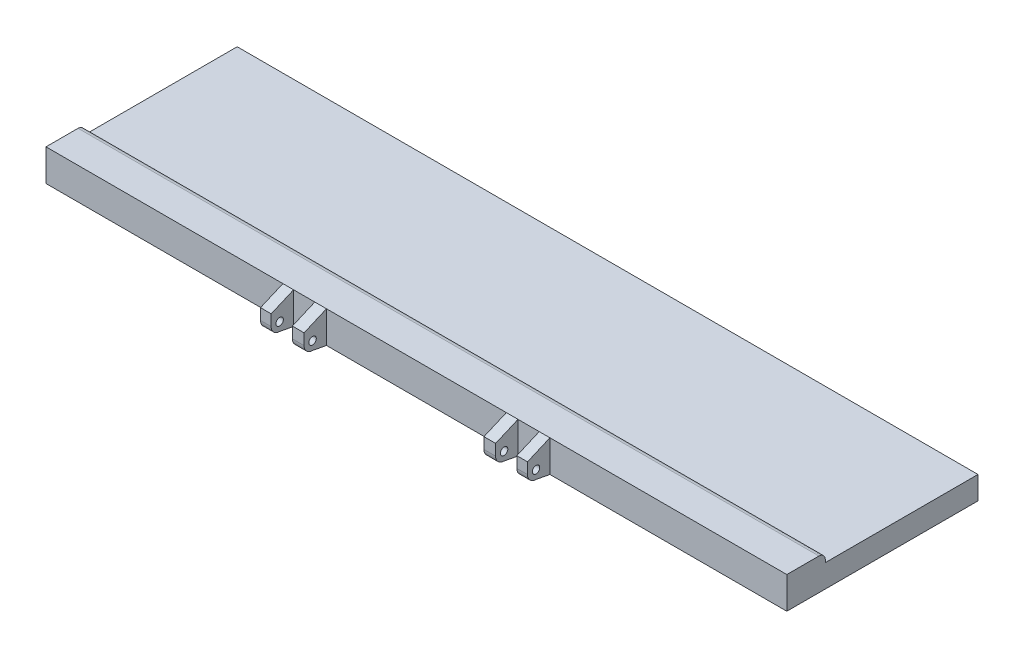
SolidWorks part; units mm, degrees
ref_plane "Front Plane" through (0, 0, 0) normal (0, 0, 1) x (1, 0, 0)
ref_plane "Top Plane" through (0, 0, 0) normal (0, 1, 0) x (1, 0, 0)
ref_plane "Right Plane" through (0, 0, 0) normal (1, 0, 0) x (0, 0, -1)
sketch "Sketch1" plane through (0, 0, 0) normal (0, 1, 0) x (1, 0, 0)
  line L0 (0, -76.945) -> (-70.693, -76.945) construction
  line L1 (-291.17, 76.945) -> (291.17, 76.945)
  line L2 (-291.17, 76.945) -> (-291.17, -76.945)
  line L3 (-291.17, -76.945) -> (291.17, -76.945)
  line L4 (291.17, 76.945) -> (291.17, -76.945)
  line L5 (-291.17, 76.945) -> (291.17, -76.945) construction
  line L6 (-291.17, -76.945) -> (291.17, 76.945) construction
  line L7 (0, 0) -> (0, -76.945) construction
  line L8 (-104.9432, -85.7514) -> (-96.5524, -85.7514) construction
  line L9 (-70.693, -76.945) -> (-104.9432, -76.945)
  line L10 (-70.693, -76.945) -> (-70.693, -94.5577)
  line L11 (-70.693, -94.5577) -> (-104.9432, -94.5577)
  line L12 (-104.9432, -76.945) -> (-104.9432, -94.5577)
  line L13 (-96.5524, -85.7514) -> (-79.8666, -85.7514) construction
  line L14 (96.5524, -94.5577) -> (79.8666, -94.5577)
  line L15 (-96.5524, -76.945) -> (-79.8666, -76.945)
  line L16 (-96.5524, -76.945) -> (-96.5524, -94.5577)
  line L17 (-96.5524, -94.5577) -> (-79.8666, -94.5577)
  line L18 (-79.8666, -76.945) -> (-79.8666, -94.5577)
  line L19 (-96.5524, -76.945) -> (-79.8666, -94.5577) construction
  line L20 (-96.5524, -94.5577) -> (-79.8666, -76.945) construction
  line L21 (79.8666, -76.945) -> (79.8666, -94.5577)
  line L22 (96.5524, -76.945) -> (79.8666, -76.945)
  line L23 (96.5524, -76.945) -> (96.5524, -94.5577)
  line L24 (70.693, -94.5577) -> (104.9432, -94.5577)
  line L25 (104.9432, -76.945) -> (104.9432, -94.5577)
  line L26 (70.693, -76.945) -> (104.9432, -76.945)
  line L27 (70.693, -76.945) -> (70.693, -94.5577)
  point P0 (0, 0)
  point P14 (-88.2095, -85.7514)
  dimension "D1" = 153.89
  dimension "D2" = 582.34
  dimension "D3" = 34.2502
extrude "Boss-Extrude1" add sketch "Sketch1" along normal blind 25 contours L4 L1 L2 L3 L9 | L25 L3 L23 L24 | L3 L27 L24 L21 | L3 L18 L11 L10 | L16 L3 L12 L11
sketch "Sketch2" plane through (104.9432, 0, 0) normal (1, 0, 0) x (0, 0, -1)
  circle A0 centre (-87.8824, 8.7487) radius 2.911
  dimension "D1" = 5.8221
extrude "Cut-Extrude1" cut sketch "Sketch2" against normal through all
sketch "Sketch3" plane through (104.9432, 0, 0) normal (1, 0, 0) x (0, 0, -1)
  line L0 (-87.8824, 2.0735) -> (-76.945, 0)
  line L1 (-76.945, 0) -> (-94.5577, 0) construction
  line L2 (-87.8824, 0) -> (-94.5577, 0)
  line L3 (-94.5577, 0) -> (-94.5577, 17.4341)
  line L4 (-94.5577, 25) -> (-94.5577, 0) construction
  line L5 (-94.5577, 17.4341) -> (-76.945, 25)
  line L6 (-76.945, 25) -> (-94.5577, 25)
  line L7 (-76.945, 25) -> (-94.5577, 25) construction
  line L8 (-94.5577, 25) -> (-94.5577, 17.4341)
  arc A1 (-87.8824, 2.0735) -> (-94.5577, 8.7171) centre (-87.8983, 8.7329) cw
extrude "Cut-Extrude2" cut sketch "Sketch3" against normal through all
sketch "Sketch4" plane through (0, 25, 0) normal (0, 1, 0) x (1, 0, 0)
  line L0 (-291.17, -46.7171) -> (291.17, -46.7171)
  line L1 (-291.17, -46.7171) -> (-291.17, 76.9529)
  line L2 (291.17, -46.7171) -> (291.17, 76.9529)
  line L3 (-291.17, 76.9529) -> (291.17, 76.9529)
  line L4 (-291.17, 76.945) -> (-291.17, -76.945) construction
  line L5 (291.17, 76.945) -> (291.17, -76.945) construction
extrude "Cut-Extrude3" cut sketch "Sketch4" against normal blind 7
fillet "Fillet1" radius 5 1 edges at (0, 25, 46.7171)
sketch "Sketch5" plane through (0, 18, 0) normal (0, 1, 0) x (1, 0, 0)
  line L0 (291.17, -46.7171) -> (291.17, 76.945) construction
  line L1 (-291.17, 76.945) -> (291.17, 76.945)
  line L2 (-291.17, 76.945) -> (-291.17, 73.3326)
  line L3 (-291.17, 73.3326) -> (291.17, 73.3326)
  line L4 (291.17, 76.945) -> (291.17, 73.3326)
extrude "Cut-Extrude4" cut sketch "Sketch5" against normal through all
